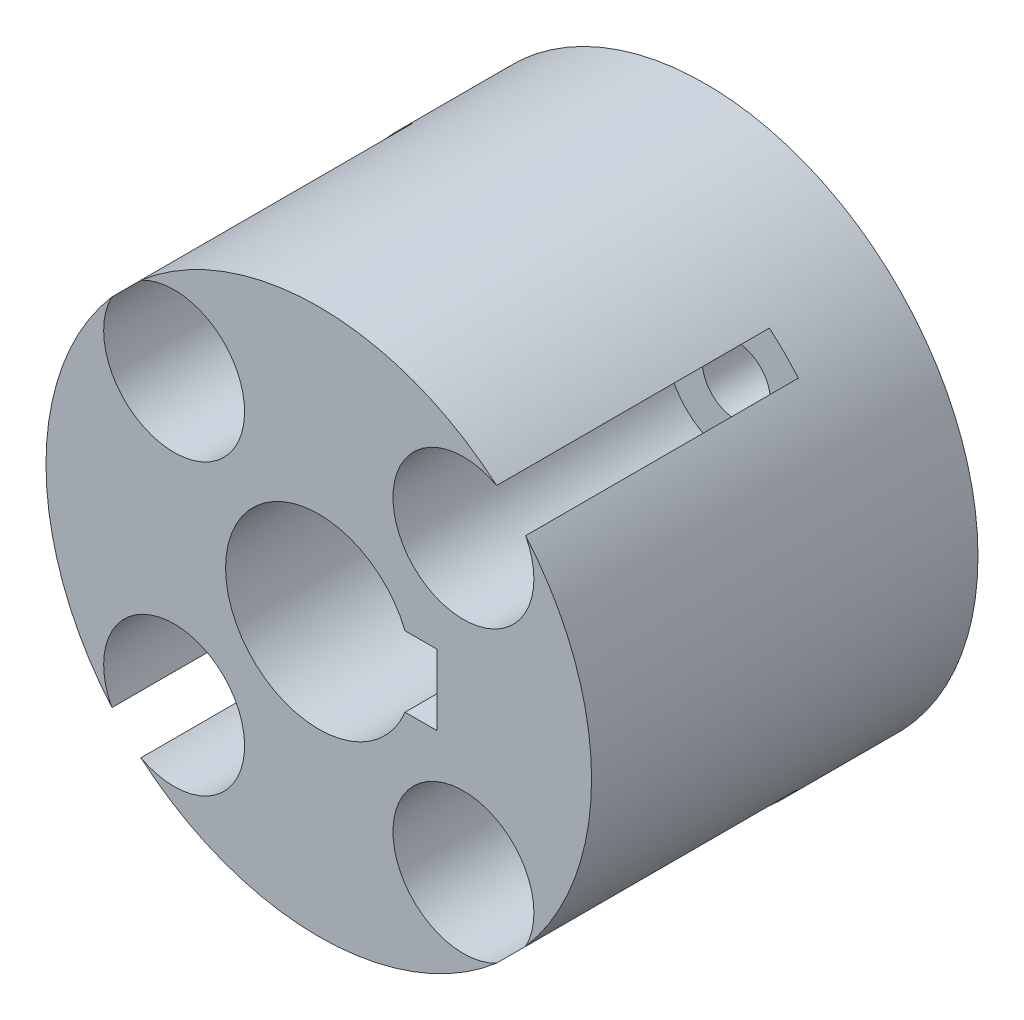
SolidWorks part; units mm, degrees
ref_plane "Ebene vorne" through (0, 0, 0) normal (0, 0, 1) x (1, 0, 0)
ref_plane "Ebene oben" through (0, 0, 0) normal (0, 1, 0) x (1, 0, 0)
ref_plane "Ebene rechts" through (0, 0, 0) normal (1, 0, 0) x (0, 0, -1)
sketch "Skizze1" plane through (0, 0, 0) normal (0, 0, 1) x (1, 0, 0)
  line L0 (0, 0) -> (6.364, 6.364) construction
  line L1 (-4.1, 0) -> (-4.1, 1.9728) construction
  line L2 (3, -1.55) -> (5.2, -1.55)
  line L3 (3, -1.55) -> (3, 1.55)
  line L4 (3, 1.55) -> (5.2, 1.55)
  line L5 (5.2, -1.55) -> (5.2, 1.55)
  line L6 (3, -1.55) -> (5.2, 1.55) construction
  line L7 (3, 1.55) -> (5.2, -1.55) construction
  circle A0 centre (0, 0) radius 12
  circle A1 centre (0, 0) radius 9
  circle A2 centre (6.364, 6.364) radius 1.5
  circle A3 centre (6.364, -6.364) radius 1.5
  circle A4 centre (-6.364, -6.364) radius 1.5
  circle A5 centre (-6.364, 6.364) radius 1.5
  circle A6 centre (0, 0) radius 4.1
  point P7 (4.1, 0)
  point P15 (0, 0)
  dimension "D1" = 24
  dimension "D2" = 18
  dimension "D3" = 4
  dimension "D4" = 8.2
  dimension "D5" = 3.1
  dimension "D6" = 9.3
extrude "Aufsatz-Linear austragen1" add sketch "Skizze1" along normal blind 17 contours A0 A5 A1 A2 A3 A4 | A5 A1 A4 A3 A2 A6 L4 L5 L2
sketch "Skizze2" plane through (0, 0, 17) normal (0, 0, 1) x (1, 0, 0)
  circle A0 centre (-6.364, 6.364) radius 3.1
  circle A1 centre (6.364, 6.364) radius 3.1
  circle A2 centre (6.364, -6.364) radius 3.1
  circle A3 centre (-6.364, -6.364) radius 3.1
  point P12 (0, 0)
  dimension "D1" = 6.2
  dimension "D2" = 4
extrude "Schnitt-Linear austragen2" cut sketch "Skizze2" against normal offset from surface (12 mm away) 5 up to face at (-4.864, 6.364, 0)
